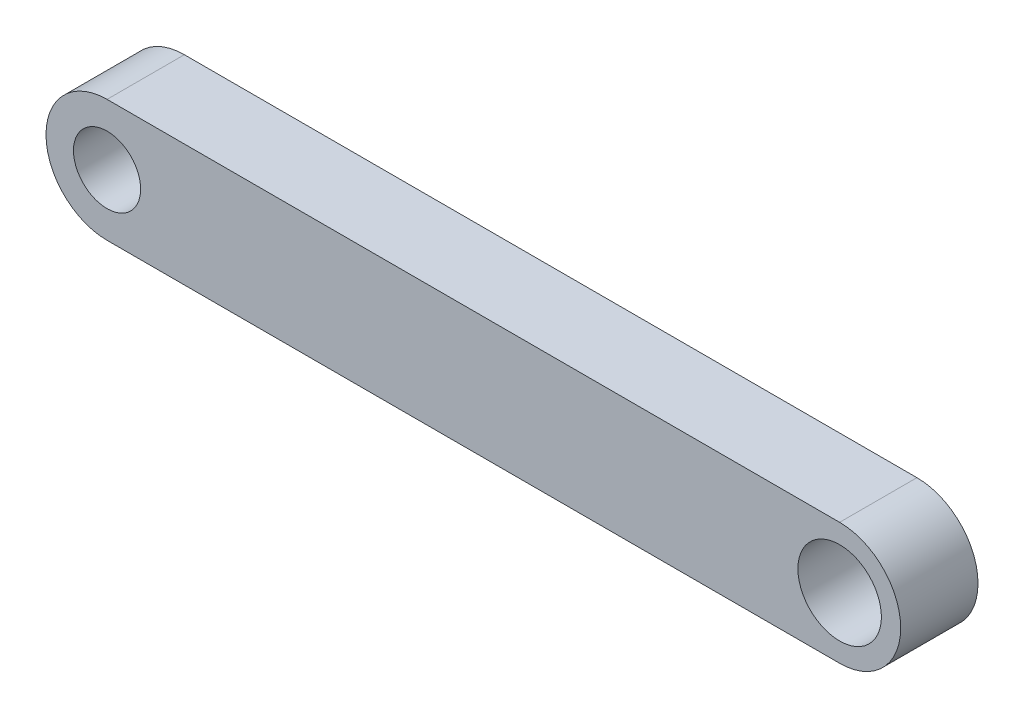
SolidWorks part; units mm, degrees
material "Anycubic PLA V3.0"
ref_plane "Front Plane" through (0, 0, 0) normal (0, 0, 1) x (1, 0, 0)
ref_plane "Top Plane" through (0, 0, 0) normal (0, 1, 0) x (1, 0, 0)
ref_plane "Right Plane" through (0, 0, 0) normal (1, 0, 0) x (0, 0, -1)
sketch "Sketch1" plane through (0, 0, 0) normal (0, 0, 1) x (1, 0, 0)
  line L0 (0, 3) -> (-36, 3)
  line L1 (0, -3) -> (-36, -3)
  line L2 (-18, 3) -> (-18, -3) construction
  line L3 (0, 3) -> (0, -3) construction
  circle A0 centre (0, 0) radius 2.05
  arc A1 (0, -3) -> (0, 3) centre (0, 0) ccw
  arc A2 (-36, -3) -> (-36, 3) centre (-36, 0) cw
  circle A3 centre (-36, 0) radius 1.65
  dimension "D1" = 4.1
  dimension "D2" = 6
  dimension "D4" = 3.3
  dimension "D3" = 36
extrude "Boss-Extrude1" add sketch "Sketch1" along normal blind 3.8
